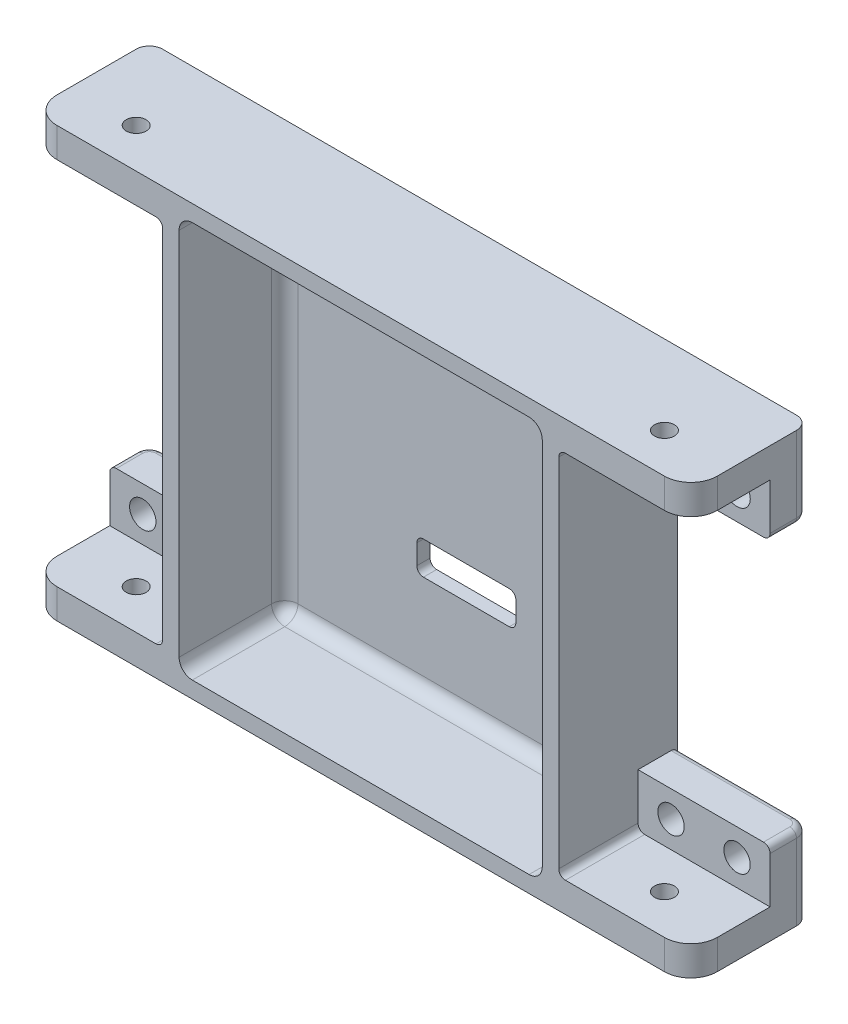
SolidWorks part; units mm, degrees
ref_plane "前视基准面" through (0, 0, 0) normal (0, 0, 1) x (1, 0, 0)
ref_plane "上视基准面" through (0, 0, 0) normal (0, 1, 0) x (1, 0, 0)
ref_plane "右视基准面" through (0, 0, 0) normal (1, 0, 0) x (0, 0, -1)
sketch "草图1" plane through (0, 0, 0) normal (0, 0, 1) x (1, 0, 0)
  line L1 (-50, -32.5) -> (50, -32.5)
  line L2 (-50, -32.5) -> (-50, 32.5)
  line L3 (-50, 32.5) -> (50, 32.5)
  line L4 (50, -32.5) -> (50, 32.5)
  line L5 (-50, -32.5) -> (50, 32.5) construction
  line L6 (-50, 32.5) -> (50, -32.5) construction
  point P0 (0, 0)
  dimension "D1" = 65
  dimension "D2" = 100
extrude "凸台-拉伸1" add sketch "草图1" along normal blind 18
sketch "草图2" plane through (0, 0, 18) normal (0, 0, 1) x (1, 0, 0)
  line L1 (-27.5, -30) -> (27.5, -30)
  line L2 (-27.5, -30) -> (-27.5, 30)
  line L3 (-27.5, 30) -> (27.5, 30)
  line L4 (27.5, -30) -> (27.5, 30)
  line L5 (-27.5, -30) -> (27.5, 30) construction
  line L6 (-27.5, 30) -> (27.5, -30) construction
  point P0 (0, 0)
  dimension "D1" = 55
  dimension "D2" = 60
extrude "切除-拉伸1" cut sketch "草图2" against normal blind 16
sketch "草图3" plane through (0, 0, 2) normal (0, 0, 1) x (1, 0, 0)
  line L0 (-27.5, -30) -> (27.5, -30) construction
  line L1 (-7.5, -15) -> (7.5, -15)
  line L2 (-7.5, -15) -> (-7.5, -10)
  line L3 (-7.5, -10) -> (7.5, -10)
  line L4 (7.5, -15) -> (7.5, -10)
  line L5 (-7.5, -15) -> (7.5, -10) construction
  line L6 (-7.5, -10) -> (7.5, -15) construction
  point P0 (0, -12.5)
  dimension "D1" = 15
  dimension "D2" = 5
  dimension "D3" = 15
extrude "切除-拉伸2" cut sketch "草图3" against normal through all
sketch "草图4" plane through (0, 0, 18) normal (0, 0, 1) x (1, 0, 0)
  line L0 (0, 0) -> (50, 0) construction
  line L1 (50, -32.5) -> (50, 32.5) construction
  line L3 (30, -28) -> (50, -28)
  line L4 (30, -28) -> (30, 28)
  line L5 (30, 28) -> (50, 28)
  line L6 (50, -28) -> (50, 28)
  line L7 (30, -28) -> (50, 28) construction
  line L8 (30, 28) -> (50, -28) construction
  point P5 (40, 0)
  dimension "D1" = 20
  dimension "D2" = 56
extrude "切除-拉伸3" cut sketch "草图4" against normal offset from surface (12 mm away) 6 up to face at (0, -12.5, 0)
sketch "草图5" plane through (0, 0, 6) normal (0, 0, 1) x (1, 0, 0)
  line L0 (0, 0) -> (50, 0) construction
  line L1 (50, -28) -> (50, 28) construction
  line L2 (30, 28) -> (30, -28) construction
  line L3 (30, -20) -> (50, -20)
  line L4 (30, -20) -> (30, 20)
  line L5 (30, 20) -> (50, 20)
  line L6 (50, -20) -> (50, 20)
  line L7 (30, -20) -> (50, 20) construction
  line L8 (30, 20) -> (50, -20) construction
  point P5 (40, 0)
  dimension "D1" = 40
extrude "切除-拉伸4" cut sketch "草图5" against normal through all
sketch "草图6" plane through (0, 0, 6) normal (0, 0, 1) x (1, 0, 0)
  line L0 (50, 20) -> (30, 20) construction
  line L1 (50, 20) -> (50, 28) construction
  line L2 (0, 0) -> (63.6012, 0) construction
  circle A0 centre (45, 24) radius 2
  circle A1 centre (35, 24) radius 2
  circle A2 centre (35, -24) radius 2
  circle A3 centre (45, -24) radius 2
  dimension "D1" = 4
  dimension "D2" = 5
  dimension "D3" = 10
  dimension "D4" = 4
extrude "切除-拉伸5" cut sketch "草图6" against normal through all
sketch "草图7" plane through (0, 32.5, 0) normal (0, 1, 0) x (1, 0, 0)
  line L0 (50, -18) -> (50, 0) construction
  line L1 (50, -18) -> (-50, -18) construction
  circle A0 centre (40, -12) radius 1.5
  dimension "D1" = 10
  dimension "D2" = 6
  dimension "D3" = 3
extrude "切除-拉伸6" cut sketch "草图7" against normal through all
mirror "镜向1" about plane through (0, 0, 0) normal (1, 0, 0) of "切除-拉伸6", "切除-拉伸5", "切除-拉伸4", "切除-拉伸3"
fillet "圆角1" radius 2 8 edges at (27.5, 0, 2) (0, 30, 2) (-27.5, 0, 2) (0, -30, 2) (27.5, 30, 10) (-27.5, 30, 10) (27.5, -30, 10) (-27.5, -30, 10)
fillet "圆角2" radius 1 4 edges at (7.5, -15, 1) (-7.5, -10, 1) (7.5, -10, 1) (-7.5, -15, 1)
fillet "圆角3" radius 4 4 edges at (-50, 30.25, 18) (-50, -30.25, 18) (50, -30.25, 18) (50, 30.25, 18)
fillet "圆角4" radius 2 4 edges at (-50, 26.25, 0) (-50, -26.25, 0) (50, -26.25, 0) (50, 26.25, 0)
fillet "圆角5" radius 1 16 edges at (39, 20, 0) (49.4142, 20, 0.5858) (39, -20, 0) (49.4142, -20, 0.5858) (-39, -20, 0) (-49.4142, -20, 0.5858) (-39, 20, 0) (-49.4142, 20, 0.5858) (50, 20, 4) (50, -20, 4) (-50, -20, 4) (-50, 20, 4) (-30, 28, 12) (-30, -28, 12) (30, -28, 12) (30, 28, 12)
